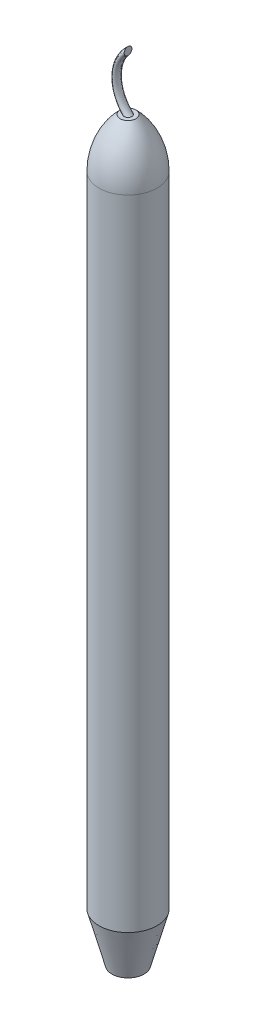
SolidWorks part; units mm, degrees
ref_plane "Front Plane" through (0, 0, 0) normal (0, 0, 1) x (1, 0, 0)
ref_plane "Top Plane" through (0, 0, 0) normal (0, 1, 0) x (1, 0, 0)
ref_plane "Right Plane" through (0, 0, 0) normal (1, 0, 0) x (0, 0, -1)
sketch "Sketch1" plane through (0, 0, 0) normal (0, 0, 1) x (1, 0, 0)
  line L0 (0, 0) -> (0, 380)
  line L1 (0, 380) -> (4, 380)
  line L2 (15, 354.5245) -> (15, 25)
  line L3 (0, 0) -> (8.3013, 0)
  line L4 (8.3013, 0) -> (15, 25)
  arc A1 (4, 380) -> (15, 354.5245) centre (-20, 354.5245) cw
  dimension "D1" = 380
  dimension "D2" = 4
  dimension "D4" = 25
  dimension "D5" = 15
revolve "Revolve1" add sketch "Sketch1" angle 360 about L0
sketch "Sketch7" plane through (0, 380, 0) normal (0, 1, 0) x (1, 0, 0)
  circle A0 centre (0, 0) radius 2
  dimension "D1" = 4
sketch "Sketch11" plane through (0, 0, 0) normal (0, 0, 1) x (1, 0, 0)
  line L0 (2, 380) -> (-2, 380) construction
  arc A0 (0, 380) -> (0, 408.2843) centre (14.1421, 394.1421) cw
  dimension "D1" = 20
sweep "Sweep6" add profiles "Sketch7" path "Sketch11"
